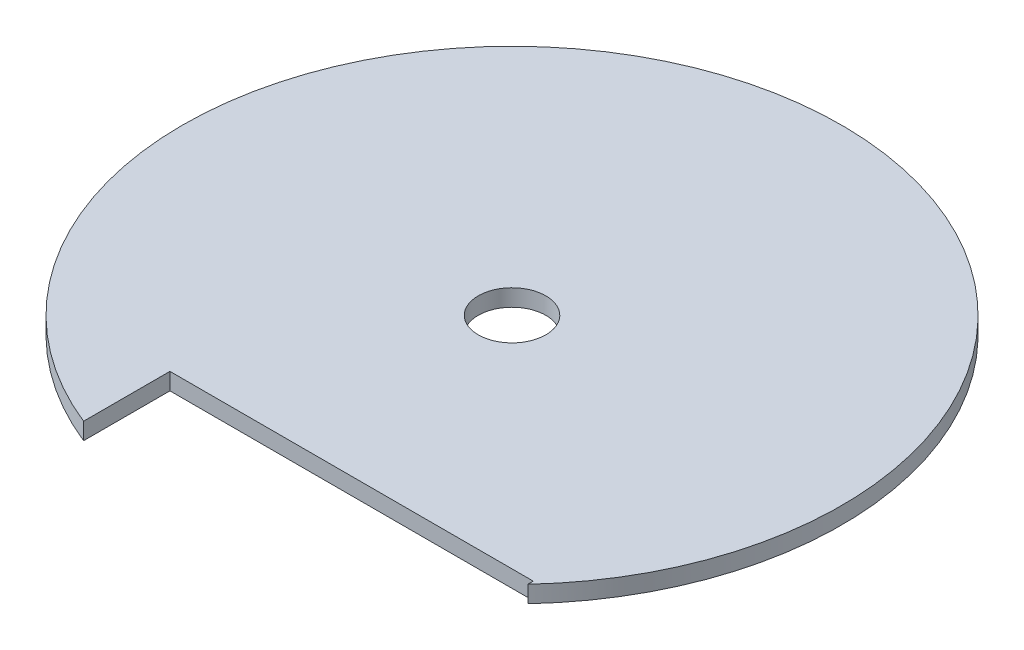
SolidWorks part; units mm, degrees
ref_plane "Front Plane" through (0, 0, 0) normal (0, 0, 1) x (1, 0, 0)
ref_plane "Top Plane" through (0, 0, 0) normal (0, 1, 0) x (1, 0, 0)
ref_plane "Right Plane" through (0, 0, 0) normal (1, 0, 0) x (0, 0, -1)
sketch "Sketch1" plane through (0, 0, 0) normal (0, 1, 0) x (1, 0, 0)
  circle A0 centre (0, 0) radius 39
  circle A1 centre (0, 0) radius 4
  dimension "D1" = 8
  dimension "D2" = 78
extrude "Boss-Extrude1" add sketch "Sketch1" along normal blind 2
sketch "Sketch2" plane through (0, 2, 0) normal (0, 1, 0) x (1, 0, 0)
  line L0 (0, 0) -> (7, 0) construction
  line L1 (7, 0) -> (7, -47.4868) construction
  line L2 (7, -47.4868) -> (0, 0) construction
  line L3 (-14.5, -68.9868) -> (28.5, -68.9868)
  line L4 (-14.5, -68.9868) -> (-14.5, -25.9868)
  line L5 (-14.5, -25.9868) -> (28.5, -25.9868)
  line L6 (28.5, -68.9868) -> (28.5, -25.9868)
  line L7 (-14.5, -68.9868) -> (28.5, -25.9868) construction
  line L8 (-14.5, -25.9868) -> (28.5, -68.9868) construction
  dimension "D1" = 43
  dimension "D2" = 43
  dimension "D3" = 48
  dimension "D4" = 7
extrude "Cut-Extrude1" cut sketch "Sketch2" against normal through all
